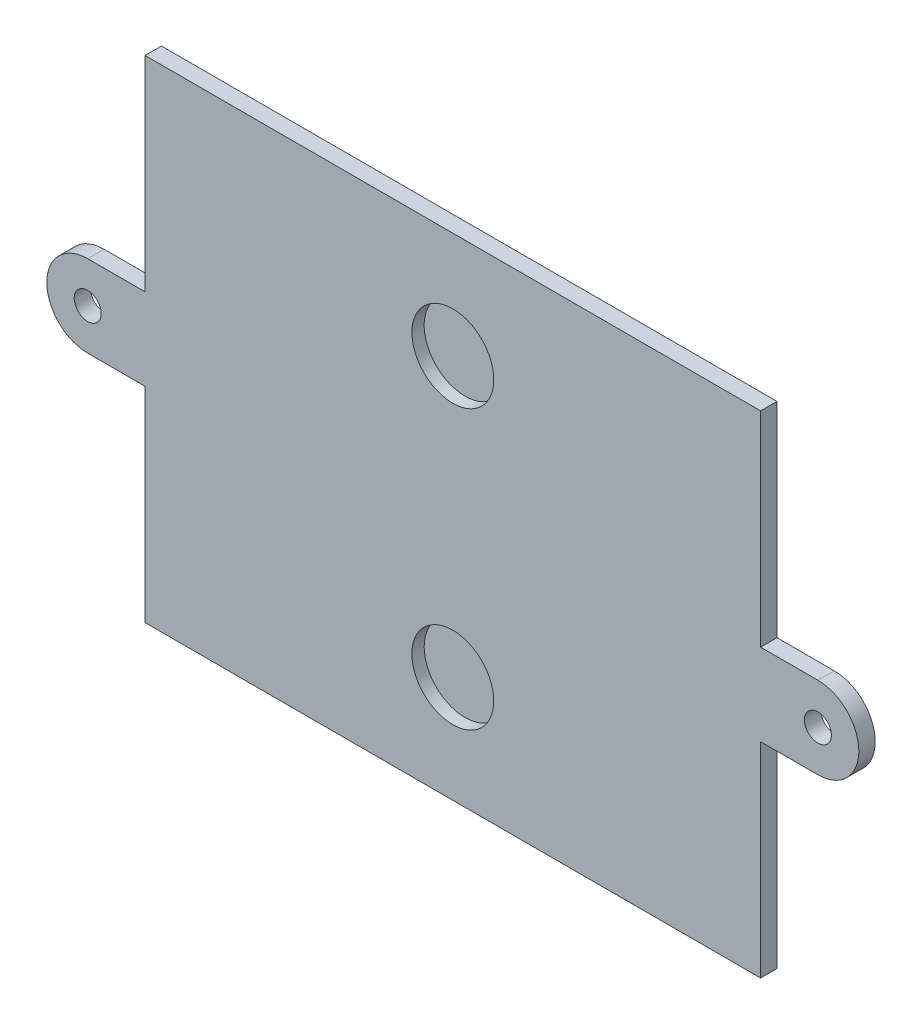
SolidWorks part; units mm, degrees
ref_plane "Front Plane" through (0, 0, 0) normal (0, 0, 1) x (1, 0, 0)
ref_plane "Top Plane" through (0, 0, 0) normal (0, 1, 0) x (1, 0, 0)
ref_plane "Right Plane" through (0, 0, 0) normal (1, 0, 0) x (0, 0, -1)
sketch "Sketch2" plane through (0, 0, 0) normal (0, 0, 1) x (1, 0, 0)
  line L0 (37.6, 60) -> (37.6, 0) construction
  line L1 (0, 0) -> (75.2, 0)
  line L2 (0, 0) -> (0, 60)
  line L3 (0, 60) -> (75.2, 60)
  line L4 (75.2, 0) -> (75.2, 60)
  line L5 (0, 30) -> (75.2, 30) construction
  line L6 (0, 35) -> (-7, 35)
  line L7 (-7, 25) -> (0, 25)
  line L8 (0, 25) -> (0, 35)
  line L9 (82.2, 25) -> (75.2, 25)
  line L10 (75.2, 35) -> (82.2, 35)
  line L11 (75.2, 25) -> (75.2, 35)
  arc A0 (-7, 35) -> (-7, 25) centre (-7, 30) ccw
  arc A1 (82.2, 35) -> (82.2, 25) centre (82.2, 30) cw
  circle A2 centre (-7, 30) radius 1.65
  circle A3 centre (82.2, 30) radius 1.65
  dimension "D5" = 3.3
  dimension "D6" = 3.3
  dimension "D1" = 75.2
  dimension "D2" = 60
  dimension "D3" = 10
  dimension "D4" = 7
extrude "Boss-Extrude1" add sketch "Sketch2" along normal blind 2 contours L6 A0 L7 L2 | L1 L4 L3 L2 | A1 L10 L4 L9
sketch "Sketch3" plane through (0, 0, 2) normal (0, 0, 1) x (1, 0, 0)
  line L0 (37.6, 60) -> (37.6, 0) construction
  line L1 (0, 60) -> (75.2, 60) construction
  line L2 (0, 0) -> (75.2, 0) construction
  line L3 (-12, 30) -> (87.2, 30) construction
  arc A0 (-7, 35) -> (-7, 25) centre (-7, 30) ccw construction
  arc A1 (82.2, 25) -> (82.2, 35) centre (82.2, 30) ccw construction
  circle A2 centre (37.6, 47) radius 5
  circle A3 centre (37.6, 13) radius 5
  dimension "D1" = 10
  dimension "D2" = 13
extrude "Cut-Extrude1" cut sketch "Sketch3" against normal blind 1.5
